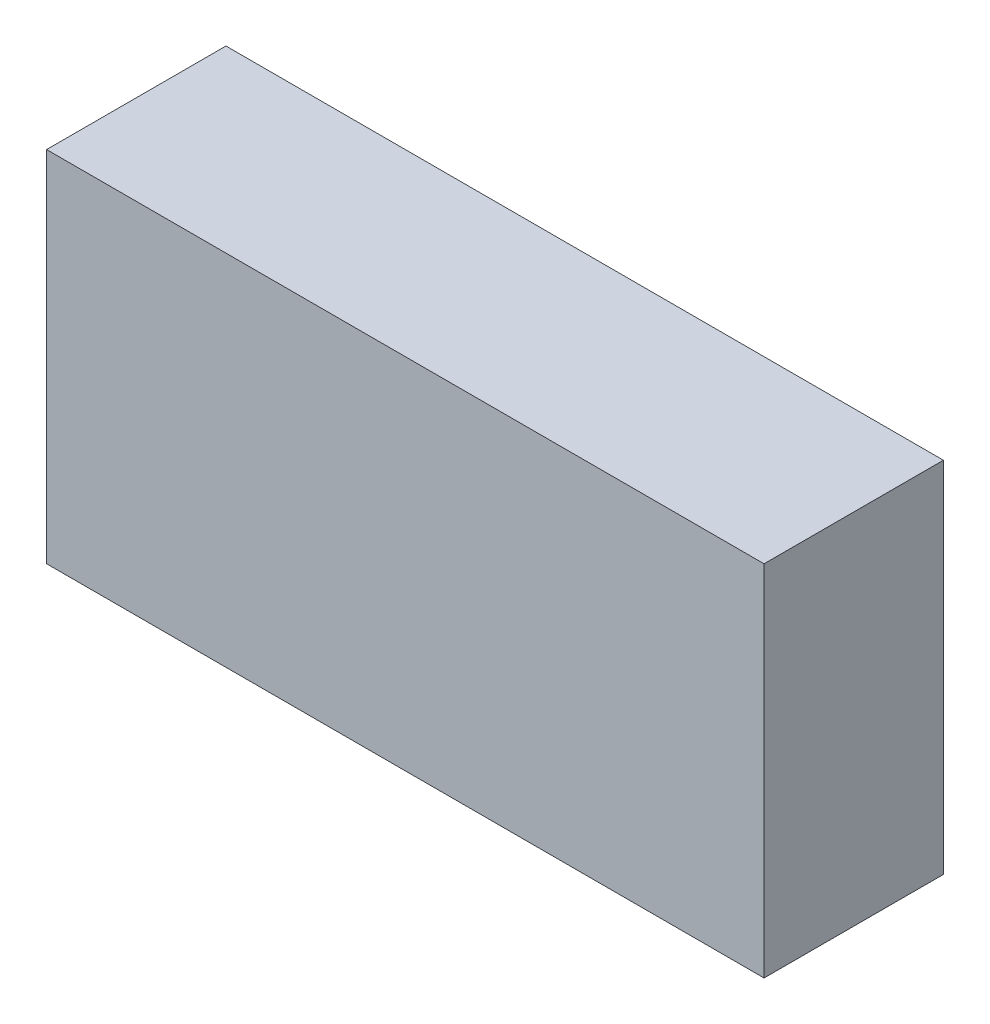
SolidWorks part; units mm, degrees
ref_plane "前视基准面" through (0, 0, 0) normal (0, 0, 1) x (1, 0, 0)
ref_plane "上视基准面" through (0, 0, 0) normal (0, 1, 0) x (1, 0, 0)
ref_plane "右视基准面" through (0, 0, 0) normal (1, 0, 0) x (0, 0, -1)
sketch "草图1" plane through (0, 0, 0) normal (0, 0, 1) x (1, 0, 0)
  line L1 (10, -5) -> (-10, -5)
  line L2 (10, -5) -> (10, 5)
  line L3 (10, 5) -> (-10, 5)
  line L4 (-10, -5) -> (-10, 5)
  line L5 (10, -5) -> (-10, 5) construction
  line L6 (10, 5) -> (-10, -5) construction
  point P0 (0, 0)
  dimension "D1" = 20
  dimension "D2" = 10
extrude "凸台-拉伸1" add sketch "草图1" along normal blind 5
